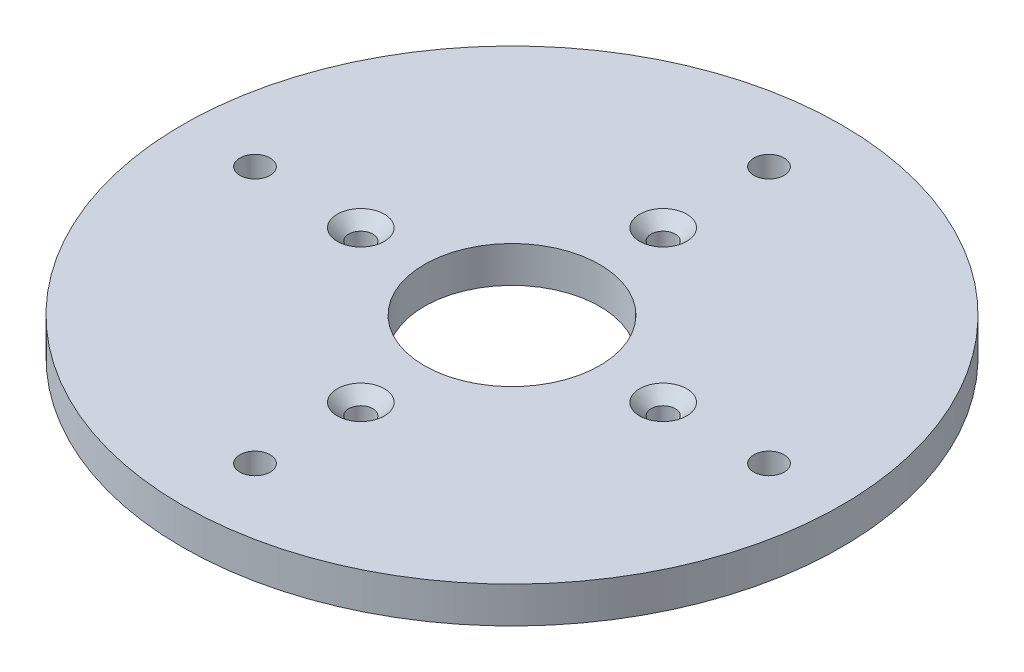
SolidWorks part; units mm, degrees
ref_plane "Спереди" through (0, 0, 0) normal (0, 0, 1) x (1, 0, 0)
ref_plane "Сверху" through (0, 0, 0) normal (0, 1, 0) x (1, 0, 0)
ref_plane "Справа" through (0, 0, 0) normal (1, 0, 0) x (0, 0, -1)
sketch "Эскиз1" plane through (0, 0, 0) normal (0, 1, 0) x (1, 0, 0)
  circle A0 centre (0, 0) radius 54.5
  circle A1 centre (0, 0) radius 14.5
  dimension "D1" = 109
  dimension "D2" = 29
extrude "Бобышка-Вытянуть1" add sketch "Эскиз1" along normal blind 6
sketch "Эскиз2" plane through (0, 6, 0) normal (0, 1, 0) x (1, 0, 0)
  line L0 (0, 42.5) -> (0, -42.5) construction
  line L1 (0, -42.5) -> (42.5, 0) construction
  line L2 (42.5, 0) -> (-42.5, 0) construction
  circle A0 centre (0, 0) radius 42.5 construction
  circle A1 centre (0, 42.5) radius 2.5
  circle A2 centre (0, -42.5) radius 2.5
  circle A3 centre (-42.5, 0) radius 2.5
  circle A4 centre (42.5, 0) radius 2.5
  dimension "D1" = 85
  dimension "D2" = 5
  dimension "D3" = 5
  dimension "D4" = 5
  dimension "D5" = 5
extrude "Вырез-Вытянуть1" cut sketch "Эскиз2" against normal blind 10
sketch "Эскиз3" plane through (0, 6, 0) normal (0, 1, 0) x (1, 0, 0)
  line L0 (0, 25) -> (0, -25) construction
  line L1 (0, -25) -> (25, 0) construction
  line L2 (25, 0) -> (-25, 0) construction
  circle A0 centre (0, 0) radius 25 construction
  circle A1 centre (0, 25) radius 2
  circle A2 centre (-25, 0) radius 2
  circle A3 centre (0, -25) radius 2
  circle A4 centre (25, 0) radius 2
  dimension "D1" = 50
  dimension "D2" = 4
  dimension "D3" = 4
  dimension "D4" = 4
  dimension "D5" = 4
extrude "Вырез-Вытянуть2" cut sketch "Эскиз3" against normal blind 10
chamfer "Фаска1" distance 1.9 angle 45 4 edges at (0, 6, -23) (25, 6, 2) (0, 6, 27) (-25, 6, 2)
